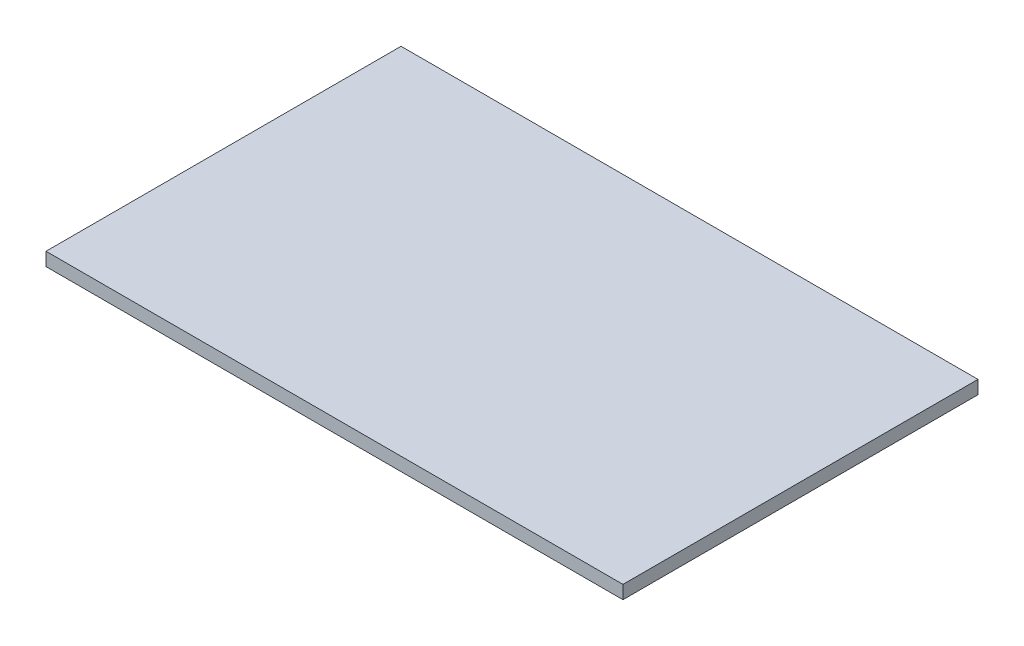
SolidWorks part; units mm, degrees
ref_plane "Front Plane" through (0, 0, 0) normal (0, 0, 1) x (1, 0, 0)
ref_plane "Top Plane" through (0, 0, 0) normal (0, 1, 0) x (1, 0, 0)
ref_plane "Right Plane" through (0, 0, 0) normal (1, 0, 0) x (0, 0, -1)
sketch "Sketch1" plane through (0, 0, 0) normal (0, 1, 0) x (1, 0, 0)
  line L1 (-65, 40) -> (65, 40)
  line L2 (-65, 40) -> (-65, -40)
  line L3 (-65, -40) -> (65, -40)
  line L4 (65, 40) -> (65, -40)
  line L5 (-65, 40) -> (65, -40) construction
  line L6 (-65, -40) -> (65, 40) construction
  point P0 (0, 0)
  dimension "D1" = 130
  dimension "D2" = 80
extrude "Boss-Extrude1" add sketch "Sketch1" along normal blind 3
